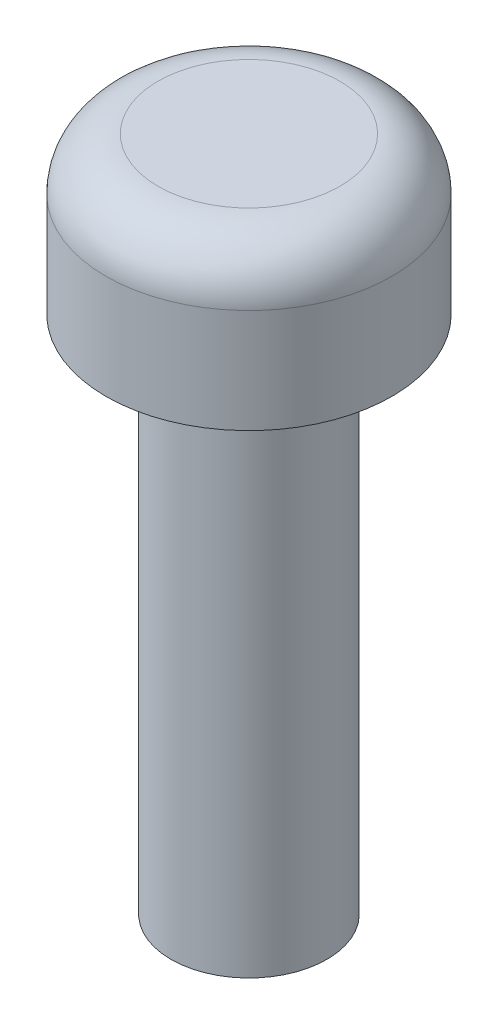
SolidWorks part; units mm, degrees
ref_plane "Front Plane" through (0, 0, 0) normal (0, 0, 1) x (1, 0, 0)
ref_plane "Top Plane" through (0, 0, 0) normal (0, 1, 0) x (1, 0, 0)
ref_plane "Right Plane" through (0, 0, 0) normal (1, 0, 0) x (0, 0, -1)
sketch "Sketch1" plane through (0, 0, 0) normal (0, 1, 0) x (1, 0, 0)
  circle A0 centre (0, 0) radius 1.5
extrude "Boss-Extrude1" add sketch "Sketch1" along normal blind 10
sketch "Sketch2" plane through (0, 10, 0) normal (0, 1, 0) x (1, 0, 0)
  circle A0 centre (0, 0) radius 2.75
extrude "Boss-Extrude2" add sketch "Sketch2" along normal blind 3
fillet "Fillet1" radius 1 1 edges at (0, 13, 2.75)
